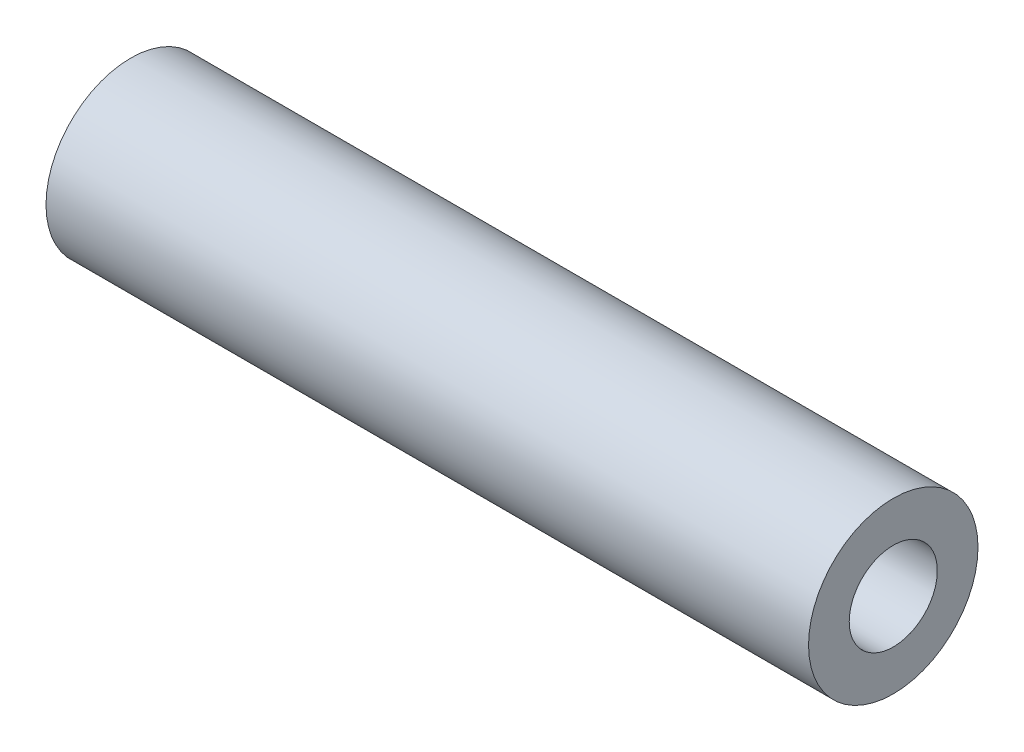
SolidWorks part; units mm, degrees
material "ABS PC"
ref_plane "前视基准面" through (0, 0, 0) normal (0, 0, 1) x (1, 0, 0)
ref_plane "上视基准面" through (0, 0, 0) normal (0, 1, 0) x (1, 0, 0)
ref_plane "右视基准面" through (0, 0, 0) normal (1, 0, 0) x (0, 0, -1)
sketch "草图1" plane through (0, 0, 0) normal (1, 0, 0) x (0, 0, -1)
  circle A0 centre (0, 0) radius 2.6
  circle A1 centre (0, 0) radius 5
  dimension "D1" = 10
  dimension "D2" = 5.2
extrude "凸台-拉伸1" add sketch "草图1" along normal blind 45
